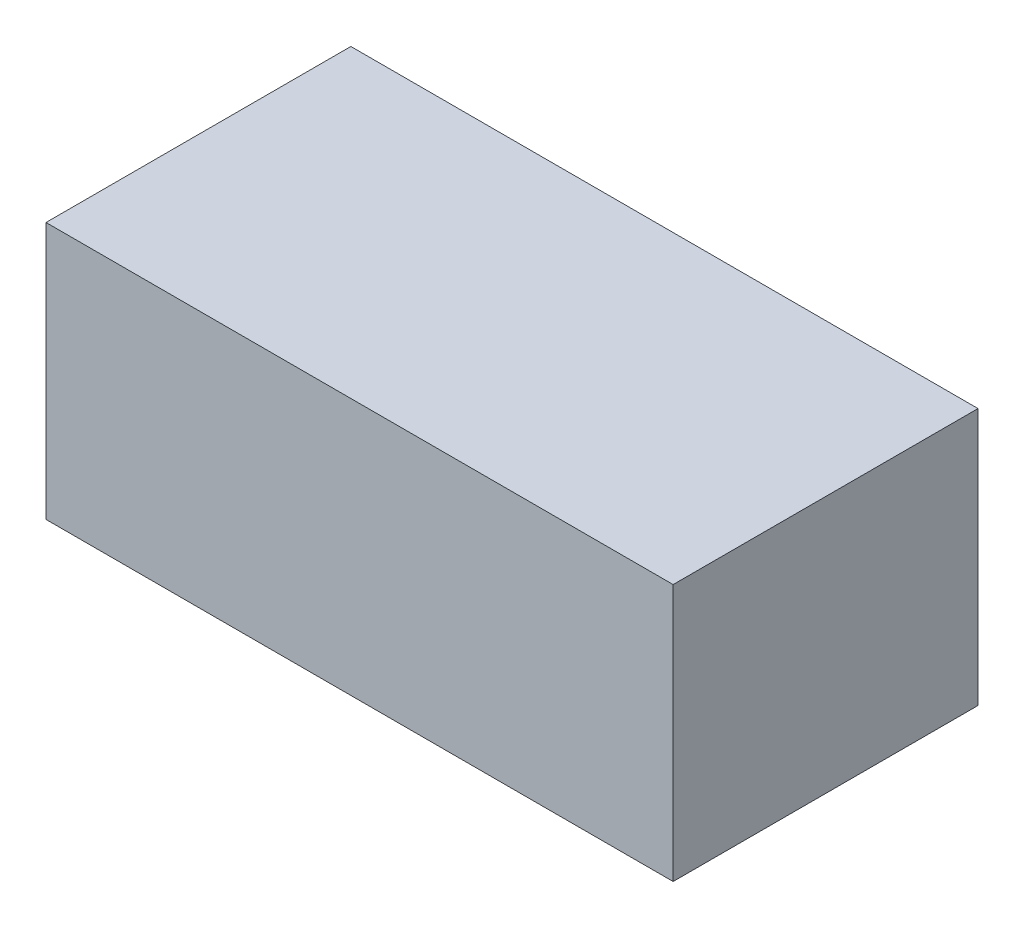
SolidWorks part; units mm, degrees
ref_plane "Front Plane" through (0, 0, 0) normal (0, 0, 1) x (1, 0, 0)
ref_plane "Top Plane" through (0, 0, 0) normal (0, 1, 0) x (1, 0, 0)
ref_plane "Right Plane" through (0, 0, 0) normal (1, 0, 0) x (0, 0, -1)
sketch "Sketch1" plane through (0, 0, 0) normal (0, 1, 0) x (1, 0, 0)
  line L1 (-914.4, 444.5) -> (914.4, 444.5)
  line L2 (-914.4, 444.5) -> (-914.4, -444.5)
  line L3 (-914.4, -444.5) -> (914.4, -444.5)
  line L4 (914.4, 444.5) -> (914.4, -444.5)
  line L5 (-914.4, 444.5) -> (914.4, -444.5) construction
  line L6 (-914.4, -444.5) -> (914.4, 444.5) construction
  point P0 (0, 0)
  dimension "D1" = 1828.8
  dimension "D2" = 889
extrude "Boss-Extrude1" add sketch "Sketch1" along normal blind 750
